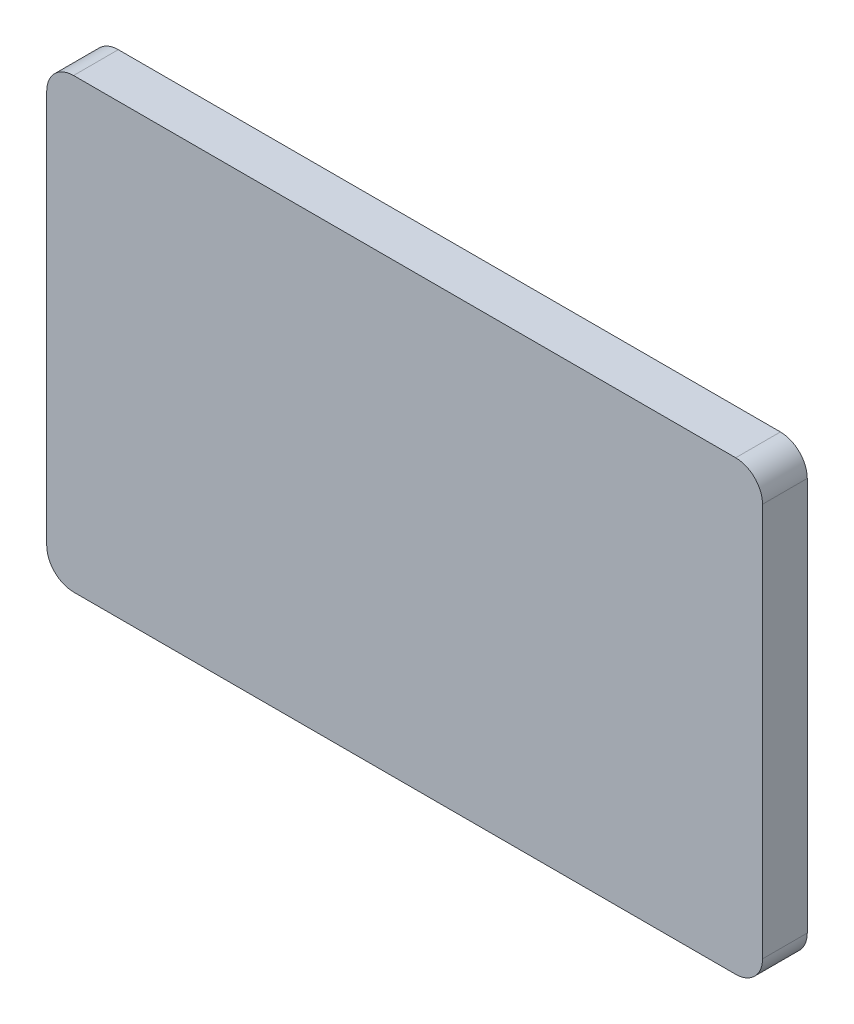
SolidWorks part; units mm, degrees
ref_plane "Front Plane" through (0, 0, 0) normal (0, 0, 1) x (1, 0, 0)
ref_plane "Top Plane" through (0, 0, 0) normal (0, 1, 0) x (1, 0, 0)
ref_plane "Right Plane" through (0, 0, 0) normal (1, 0, 0) x (0, 0, -1)
sketch "Sketch1" plane through (0, 0, 0) normal (0, 0, 1) x (1, 0, 0)
  line L1 (-40, 25) -> (40, 25)
  line L2 (-40, 25) -> (-40, -25)
  line L3 (-40, -25) -> (40, -25)
  line L4 (40, 25) -> (40, -25)
  line L5 (-40, 25) -> (40, -25) construction
  line L6 (-40, -25) -> (40, 25) construction
  point P0 (0, 0)
  dimension "D1" = 80
  dimension "D2" = 50
extrude "Boss-Extrude1" add sketch "Sketch1" along normal blind 5
fillet "Fillet1" radius 3 4 edges at (-40, 25, 2.5) (-40, -25, 2.5) (40, -25, 2.5) (40, 25, 2.5)
